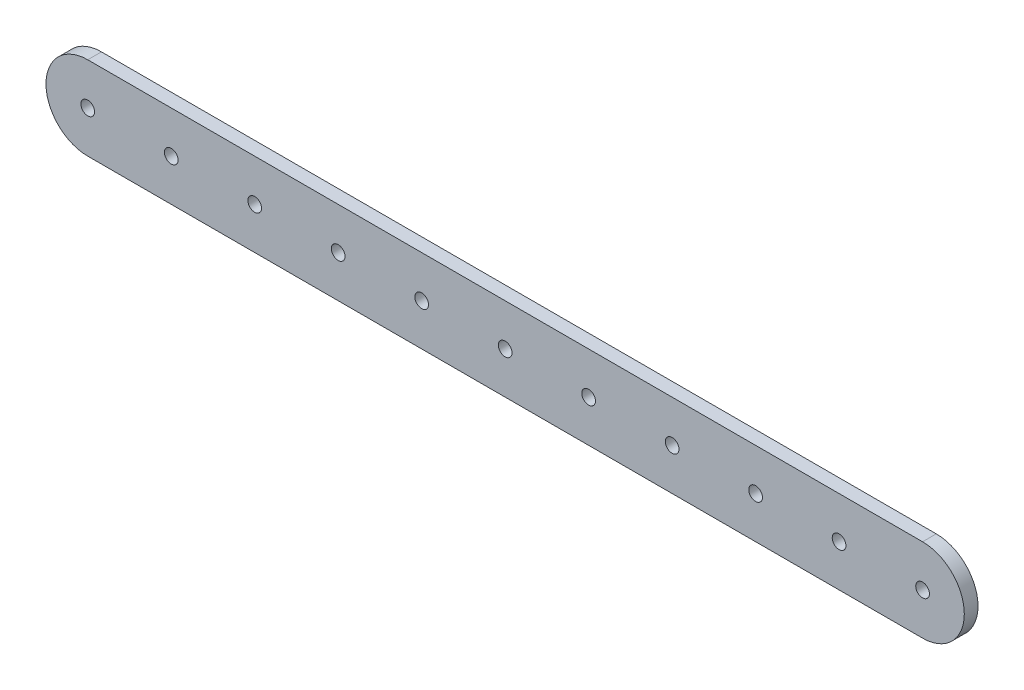
SolidWorks part; units mm, degrees
ref_plane "Front Plane" through (0, 0, 0) normal (0, 0, 1) x (1, 0, 0)
ref_plane "Top Plane" through (0, 0, 0) normal (0, 1, 0) x (1, 0, 0)
ref_plane "Right Plane" through (0, 0, 0) normal (1, 0, 0) x (0, 0, -1)
sketch "Sketch1" plane through (0, 0, 0) normal (0, 0, 1) x (1, 0, 0)
  line L0 (-1416.6273, 0) -> (1631.3727, 0) construction
  line L1 (-1416.6273, 152.4) -> (1631.3727, 152.4)
  line L2 (-1416.6273, -152.4) -> (1631.3727, -152.4)
  arc A0 (-1416.6273, 152.4) -> (-1416.6273, -152.4) centre (-1416.6273, 0) ccw
  arc A1 (1631.3727, -152.4) -> (1631.3727, 152.4) centre (1631.3727, 0) ccw
  point P3 (107.3727, 0)
  dimension "D2" = 152.4
  dimension "D1" = 3048
extrude "Boss-Extrude1" add sketch "Sketch1" along normal blind 50
sketch "Sketch2" plane through (0, 0, 50) normal (0, 0, 1) x (1, 0, 0)
  circle A0 centre (1631.3727, 0) radius 25
  dimension "D1" = 50
  dimension "D2" = 0
extrude "Cut-Extrude1" cut sketch "Sketch2" against normal up to surface (50 mm away) up to face at (107.3727, 0, 0)
pattern_linear "LPattern1" count 11 spacing 304.8 along (-1, 0, 0) of "Cut-Extrude1"
